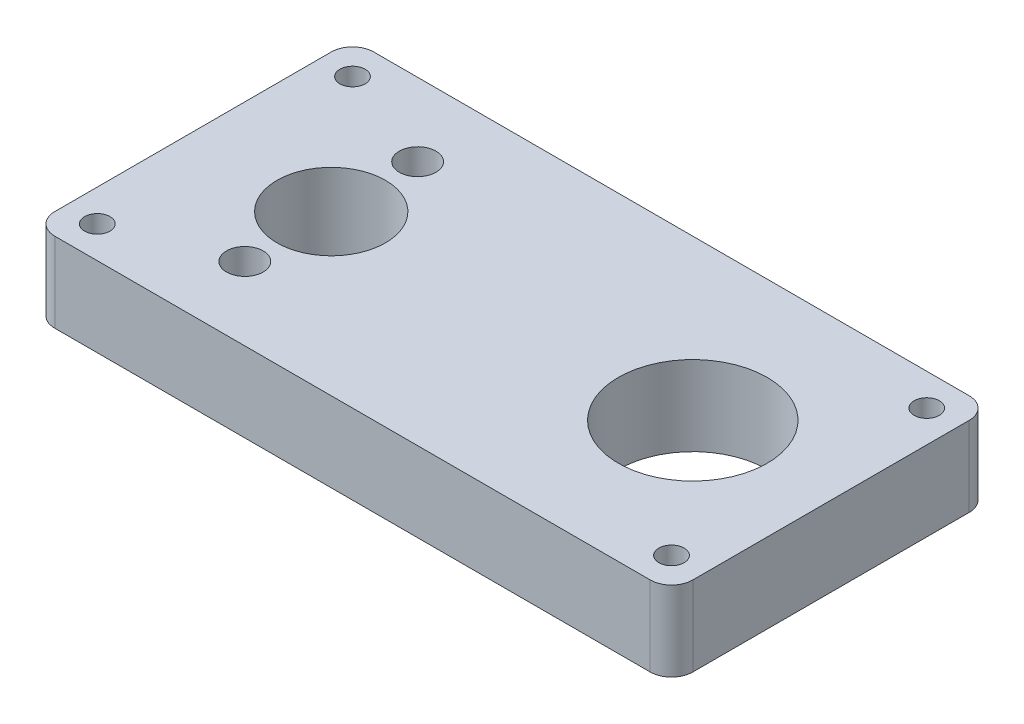
SolidWorks part; units mm, degrees
material "Acrylic (Medium-high impact)"
ref_plane "Front Plane" through (0, 0, 0) normal (0, 0, 1) x (1, 0, 0)
ref_plane "Top Plane" through (0, 0, 0) normal (0, 1, 0) x (1, 0, 0)
ref_plane "Right Plane" through (0, 0, 0) normal (1, 0, 0) x (0, 0, -1)
ref_plane "Plane1" through (0, 0, 0) normal (0, -1, 0) x (1, 0, 0)
sketch "Sketch1" plane through (0, 0, 0) normal (0, -1, 0) x (1, 0, 0)
  line L0 (-35.56, -19.05) -> (35.56, -19.05)
  line L1 (38.1, -16.51) -> (38.1, 16.51)
  line L2 (35.56, 19.05) -> (-35.56, 19.05)
  line L3 (-38.1, 16.51) -> (-38.1, -16.51)
  line L4 (0, 0) -> (0, 12.2265) construction
  line L5 (-21.59, -10.3188) -> (-21.59, 10.3188) construction
  circle A0 centre (-21.59, 0) radius 6.477
  circle A1 centre (-21.59, -10.3188) radius 2.1908
  circle A2 centre (-21.59, 10.3188) radius 2.1908
  circle A10 centre (21.59, 0) radius 8.89
  arc A13 (35.56, -19.05) -> (38.1, -16.51) centre (35.56, -16.51) ccw
  arc A14 (38.1, 16.51) -> (35.56, 19.05) centre (35.56, 16.51) ccw
  arc A15 (-35.56, 19.05) -> (-38.1, 16.51) centre (-35.56, 16.51) ccw
  arc A16 (-38.1, -16.51) -> (-35.56, -19.05) centre (-35.56, -16.51) ccw
  circle A17 centre (-21.59, 0) radius 14.2646 construction
  point P8 (-21.59, -8.128)
  point P9 (-21.59, 8.128)
  point P10 (-21.59, 0)
  dimension "D1" = 28.5293
  dimension "D5" = 2.54
  dimension "D8" = 17.78
  dimension "D9" = 12.954
  dimension "D10" = 4.3815
  dimension "D2" = 43.18
  dimension "D3" = 76.2
  dimension "D4" = 38.1
  dimension "D6" = 19.05
  dimension "D7" = 38.1
  dimension "D11" = 10.3187
extrude "Boss-Extrude1" add sketch "Sketch1" against normal blind 9.525
ref_plane "Plane2" through (0, 0, 0) normal (0, 0, 1) x (1, 0, 0)
hole_wizard "Ø1.0mm Dowel Hole1" positions "Sketch3" profile "Sketch4" hole size "Ø1.0" standard "ANSI Metric"
sketch "Sketch3" plane through (0, 9.525, 0) normal (0, 1, 0) x (1, 0, 0)
  line L0 (0, 0) -> (10.5209, 0) construction
  line L2 (0, 0) -> (0, 8.584) construction
  line L4 (-35.56, 19.05) -> (35.56, 19.05) construction
  line L5 (-38.1, -16.51) -> (-38.1, 16.51) construction
  point P0 (-34.29, 15.24)
  point P2 (-34.29, -15.24)
  point P4 (34.29, -15.24)
  point P6 (34.29, 15.24)
  dimension "D1" = 3.81
  dimension "D2" = 3.81
sketch "Sketch4" plane through (-34.29, 9.525, -15.24) normal (1, 0, 0) x (0, 0, 1)
  line L0 (0, 0) -> (0, 10.9081)
  line L1 (0, 10.9081) -> (1.5113, 10)
  line L2 (1.5113, 10) -> (1.5113, 0)
  line L5 (1.5113, 0) -> (0, 0)
  line L10 (0, 10.9081) -> (-1.5113, 10) construction
  line L11 (0, -6.35) -> (0, 107.95) construction
  dimension "Hole Dia." = 3.0226
  dimension "Hole Depth" = 10
  dimension "Drill Angle" = 118
hole_wizard "Ø1.0mm Dowel Hole2" positions "Sketch6" profile "Sketch7" hole size "Ø1.0" standard "ANSI Metric"
sketch "Sketch6" plane through (0, 6.35, 0) normal (0, 1, 0) x (1, 0, 0)
  point P0 (-34.29, 15.24)
  point P3 (34.29, 15.24)
  point P6 (34.29, -15.24)
  point P8 (-34.29, -15.24)
sketch "Sketch7" plane through (-34.29, 6.35, -15.24) normal (1, 0, 0) x (0, 0, 1)
  line L0 (0, 0) -> (0, 6.35)
  line L1 (0, 6.35) -> (1.5113, 6.35)
  line L2 (1.5113, 6.35) -> (1.5113, 0)
  line L5 (1.5113, 0) -> (0, 0)
  line L11 (0, -6.35) -> (0, 107.95) construction
  dimension "Thru Hole Dia." = 3.0226
  dimension "Thru Hole Depth" = 6.35
